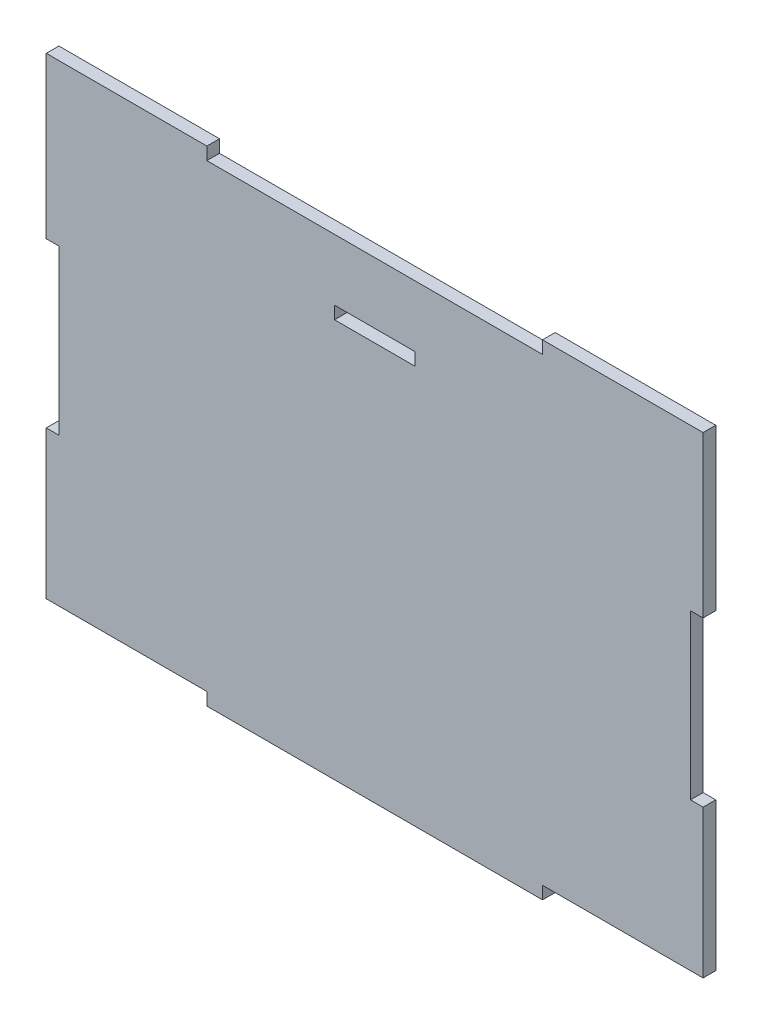
SolidWorks part; units mm, degrees
ref_plane "Front Plane" through (0, 0, 0) normal (0, 0, 1) x (1, 0, 0)
ref_plane "Top Plane" through (0, 0, 0) normal (0, 1, 0) x (1, 0, 0)
ref_plane "Right Plane" through (0, 0, 0) normal (1, 0, 0) x (0, 0, -1)
sketch "Sketch1" plane through (0, 0, 0) normal (0, 0, 1) x (1, 0, 0)
  line L0 (-26.543, 36.354) -> (26.543, 36.354)
  line L1 (-26.543, -38.354) -> (26.543, -38.354)
  line L3 (-51.943, 38.354) -> (-26.543, 38.354)
  line L4 (51.943, -36.354) -> (51.943, -12.954)
  line L5 (26.543, 38.354) -> (51.943, 38.354)
  line L6 (-51.943, 38.354) -> (51.943, 38.354) construction
  line L7 (49.943, -12.954) -> (49.943, 12.954)
  line L8 (-49.943, -36.354) -> (-26.543, -36.354)
  line L9 (-49.943, -12.954) -> (-49.943, 12.954)
  line L10 (-26.543, 38.354) -> (-26.543, 36.354)
  line L11 (26.543, 38.354) -> (26.543, 36.354)
  line L12 (-51.943, 12.954) -> (-49.943, 12.954)
  line L13 (-51.943, -12.954) -> (-49.943, -12.954)
  line L14 (51.943, 12.954) -> (51.943, 38.354)
  line L15 (51.943, -38.354) -> (51.943, 38.354) construction
  line L16 (-51.943, 12.954) -> (-51.943, 38.354)
  line L17 (-26.543, -36.354) -> (-26.543, -38.354)
  line L18 (-51.943, -38.354) -> (-51.943, 38.354) construction
  line L19 (-51.943, -38.354) -> (51.943, -38.354) construction
  line L20 (-51.943, -12.954) -> (-51.943, -36.354)
  line L21 (26.543, -36.354) -> (26.543, -38.354)
  line L22 (-51.943, -36.354) -> (-49.943, -36.354)
  line L23 (49.943, -12.954) -> (51.943, -12.954)
  line L24 (49.943, 12.954) -> (51.943, 12.954)
  line L25 (49.943, -36.354) -> (51.943, -36.354)
  line L26 (-49.943, 36.354) -> (49.943, 36.354) construction
  line L27 (-49.943, -36.354) -> (-49.943, 36.354) construction
  line L28 (49.943, -36.354) -> (49.943, 36.354) construction
  line L29 (26.543, -36.354) -> (49.943, -36.354)
  line L30 (-49.943, -36.354) -> (49.943, -36.354) construction
  line L31 (0, 36.354) -> (0, -38.354) construction
  line L32 (-51.943, 25.654) -> (51.943, 25.654) construction
  line L34 (-6.35, 24.654) -> (6.35, 24.654)
  line L35 (-6.35, 24.654) -> (-6.35, 26.654)
  line L36 (-6.35, 26.654) -> (6.35, 26.654)
  line L37 (6.35, 24.654) -> (6.35, 26.654)
  line L38 (-6.35, 24.654) -> (6.35, 26.654) construction
  line L39 (-6.35, 26.654) -> (6.35, 24.654) construction
  point P0 (0, 0)
  point P27 (0, 25.654)
  dimension "D1" = 12.7
  dimension "D2" = 103.886
  dimension "D4" = 2
  dimension "D5" = 25.4
  dimension "D6" = 25.4
  dimension "D7" = 25.4
  dimension "D3" = 2
extrude "Boss-Extrude1" add sketch "Sketch1" along normal blind 2
